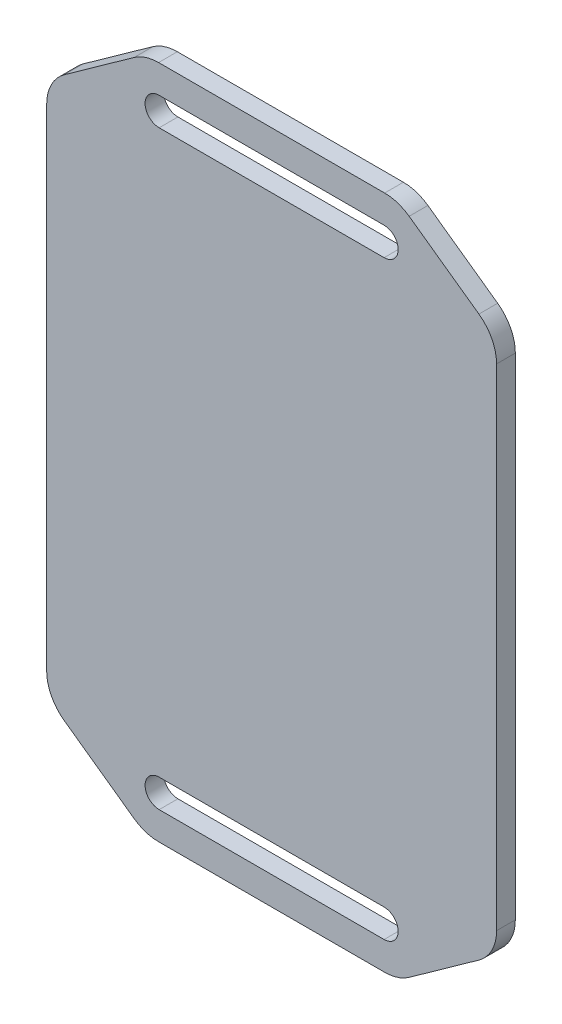
SolidWorks part; units mm, degrees
ref_plane "Alzado" through (0, 0, 0) normal (0, 0, 1) x (1, 0, 0)
ref_plane "Planta" through (0, 0, 0) normal (0, 1, 0) x (1, 0, 0)
ref_plane "Vista lateral" through (0, 0, 0) normal (1, 0, 0) x (0, 0, -1)
sketch "Croquis1" plane through (0, 0, 0) normal (0, 0, 1) x (1, 0, 0)
  line L0 (200.096, 161.8428) -> (200.096, 214.2107)
  line L1 (164.0381, 152.0271) -> (188.1539, 152.0271)
  line L2 (188.1539, 224.0264) -> (164.0381, 224.0264)
  line L9 (152.096, 161.8428) -> (152.096, 214.2107)
  line L14 (153.9804, 217.8725) -> (161.4225, 223.1882)
  line L15 (190.7695, 223.1882) -> (198.2116, 217.8725)
  line L16 (153.9804, 158.181) -> (161.4225, 152.8653)
  line L17 (190.7695, 152.8653) -> (198.2116, 158.181)
  line L18 (164.096, 158.0271) -> (188.096, 158.0271)
  line L19 (164.096, 155.0271) -> (188.096, 155.0271)
  line L20 (164.096, 221.0271) -> (188.096, 221.0271)
  line L21 (164.096, 218.0271) -> (188.096, 218.0271)
  arc A8 (153.9804, 217.8725) -> (152.096, 214.2107) centre (156.596, 214.2107) ccw
  arc A9 (164.0381, 224.0264) -> (161.4225, 223.1882) centre (164.0381, 219.5264) ccw
  arc A10 (190.7695, 223.1882) -> (188.1539, 224.0264) centre (188.1539, 219.5264) ccw
  arc A11 (200.096, 214.2107) -> (198.2116, 217.8725) centre (195.596, 214.2107) ccw
  arc A12 (198.2116, 158.181) -> (200.096, 161.8428) centre (195.596, 161.8428) ccw
  arc A13 (188.1539, 152.0271) -> (190.7695, 152.8653) centre (188.1539, 156.5271) ccw
  arc A14 (161.4225, 152.8653) -> (164.0381, 152.0271) centre (164.0381, 156.5271) ccw
  arc A15 (152.096, 161.8428) -> (153.9804, 158.181) centre (156.596, 161.8428) ccw
  arc A16 (188.096, 155.0271) -> (188.096, 158.0271) centre (188.096, 156.5271) ccw
  arc A17 (164.096, 158.0271) -> (164.096, 155.0271) centre (164.096, 156.5271) ccw
  arc A18 (188.096, 218.0271) -> (188.096, 221.0271) centre (188.096, 219.5271) ccw
  arc A19 (164.096, 221.0271) -> (164.096, 218.0271) centre (164.096, 219.5271) ccw
extrude "Extruir1" add sketch "Croquis1" along normal blind 2
